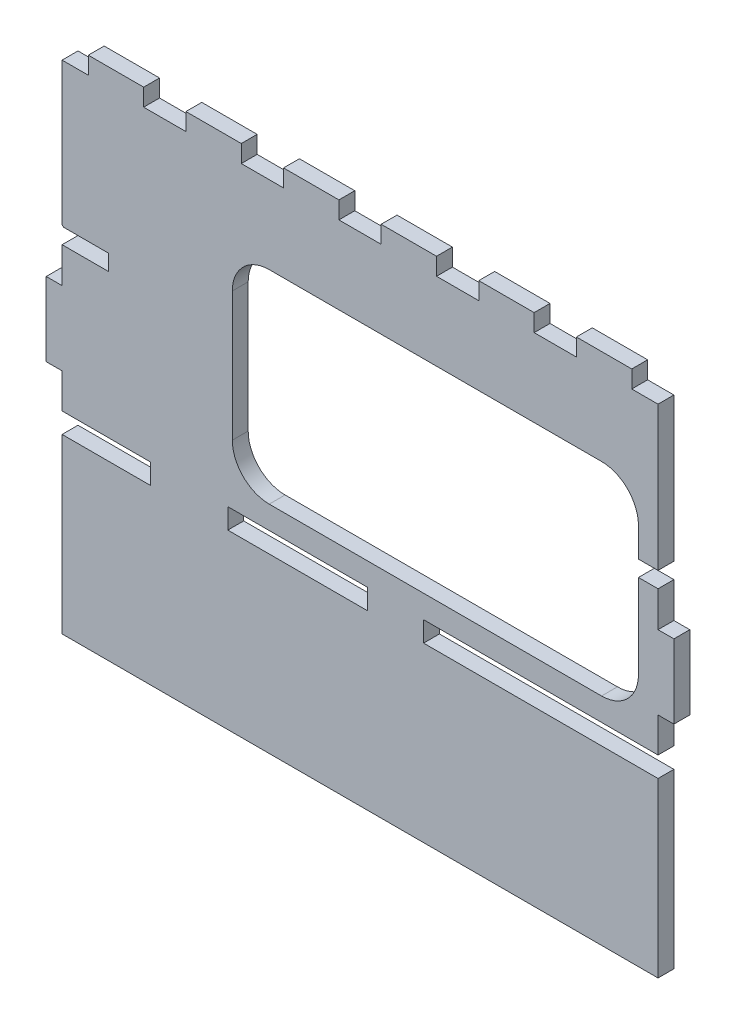
SolidWorks part; units mm, degrees
ref_plane "Front Plane" through (0, 0, 0) normal (0, 0, 1) x (1, 0, 0)
ref_plane "Top Plane" through (0, 0, 0) normal (0, 1, 0) x (1, 0, 0)
ref_plane "Right Plane" through (0, 0, 0) normal (1, 0, 0) x (0, 0, -1)
sketch "Sketch2" plane through (0, 0, 0) normal (0, 0, 1) x (1, 0, 0)
  line L1 (-73.61, 69.65) -> (-58.61, 69.65)
  line L2 (-85, 12.05) -> (-85, -7.95)
  line L3 (-80.7, -69.65) -> (80.7, -69.65)
  line L4 (85, 12.05) -> (85, -7.95)
  line L5 (32.15, 69.65) -> (47.15, 69.65)
  line L6 (58.59, 69.65) -> (73.59, 69.65)
  line L8 (-73.61, 69.65) -> (-73.61, 64.95)
  line L10 (-58.61, 69.65) -> (-58.61, 64.95)
  line L11 (-47.17, 69.65) -> (-47.17, 64.95)
  line L13 (-32.17, 69.65) -> (-32.17, 64.95)
  line L14 (-20.73, 69.65) -> (-20.73, 64.95)
  line L16 (-5.73, 69.65) -> (-5.73, 64.95)
  line L17 (5.71, 69.65) -> (5.71, 64.95)
  line L19 (20.71, 69.65) -> (20.71, 64.95)
  line L20 (32.15, 69.65) -> (32.15, 64.95)
  line L22 (47.15, 69.65) -> (47.15, 64.95)
  line L23 (58.59, 69.65) -> (58.59, 64.95)
  line L25 (73.59, 69.65) -> (73.59, 64.95)
  line L26 (-80.7, 64.95) -> (-80.7, 26.35)
  line L27 (-80.7, 64.95) -> (-80.7, 26.35) construction
  line L28 (-80.7, 12.05) -> (-85, 12.05)
  line L30 (-80.7, -7.95) -> (-85, -7.95)
  line L32 (80.7, 64.95) -> (80.7, 25.95)
  line L33 (80.7, -7.95) -> (80.7, -17.35)
  line L34 (80.7, 12.05) -> (85, 12.05)
  line L36 (80.7, -7.95) -> (85, -7.95)
  line L38 (-80.7, -7.95) -> (-80.7, -17.35)
  line L39 (5.71, 69.65) -> (20.71, 69.65)
  line L40 (-20.73, 69.65) -> (-5.73, 69.65)
  line L41 (-47.17, 69.65) -> (-32.17, 69.65)
  line L42 (80.7, 64.95) -> (73.59, 64.95)
  line L43 (58.59, 64.95) -> (47.15, 64.95)
  line L44 (60.4, 21.65) -> (75.4, 21.65) construction
  line L46 (32.15, 64.95) -> (20.71, 64.95)
  line L48 (5.71, 64.95) -> (-5.73, 64.95)
  line L50 (-20.73, 64.95) -> (-32.17, 64.95)
  line L52 (-47.17, 64.95) -> (-58.61, 64.95)
  line L53 (-73.61, 64.95) -> (-80.7, 64.95)
  line L54 (-80.318, 25.95) -> (-80.7, 26.35)
  line L57 (79.9, 25.95) -> (75.4, 25.95)
  line L59 (80.282, 21.65) -> (75.4, 21.65)
  line L60 (75.4, 25.95) -> (75.4, 21.65)
  line L65 (-68.2, 25.95) -> (-80.318, 25.95)
  line L66 (-68.2, 25.95) -> (-68.2, 21.65)
  line L67 (-68.2, 21.65) -> (-80.7, 21.65)
  line L83 (65.4, 43.85) -> (-24.6, 43.85)
  line L84 (75.4, 33.85) -> (75.4, -1.15)
  line L85 (65.4, -11.15) -> (-24.6, -11.15)
  line L86 (-34.6, 33.85) -> (-34.6, -1.15)
  line L88 (-80.7, 22.05) -> (-80.7, 21.65)
  line L89 (-80.7, 22.05) -> (-80.7, 12.05)
  line L90 (-80.7, 22.05) -> (-80.7, 12.05) construction
  line L91 (79.9, 25.95) -> (80.7, 25.95)
  line L93 (80.7, 21.65) -> (80.282, 21.65)
  line L94 (80.7, 21.65) -> (80.7, 12.05)
  line L97 (80.7, -22.85) -> (80.7, -69.65)
  line L98 (-35.818, -17.35) -> (1.952, -17.35)
  line L100 (-80.7, -22.85) -> (-80.7, -69.65)
  line L101 (80.7, -17.35) -> (17.2, -17.35)
  line L103 (80.7, -22.85) -> (17.2, -22.85)
  line L104 (17.2, -17.35) -> (17.2, -22.85)
  line L105 (1.952, -22.85) -> (1.952, -17.35)
  line L106 (-35.818, -22.85) -> (1.952, -22.85)
  line L107 (-35.818, -22.85) -> (-35.818, -17.35)
  line L109 (-80.7, -22.85) -> (-56.7296, -22.85)
  line L111 (-80.7, -17.35) -> (-56.7296, -17.35)
  line L112 (-56.7296, -22.85) -> (-56.7296, -17.35)
  arc A0 (75.4, 33.85) -> (65.4, 43.85) centre (65.4, 33.85) ccw
  arc A1 (65.4, -11.15) -> (75.4, -1.15) centre (65.4, -1.15) ccw
  arc A2 (-24.6, 43.85) -> (-34.6, 33.85) centre (-24.6, 33.85) ccw
  arc A3 (-34.6, -1.15) -> (-24.6, -11.15) centre (-24.6, -1.15) ccw
  point P1 (0, 0)
  point P50 (67.9, 21.65)
  point P59 (17.2, -20.1)
  point P64 (-16.933, -22.85)
  dimension "D16" = 10
  dimension "D17" = 90
  dimension "D1" = 0
  dimension "D2" = 161.4
  dimension "D3" = 139.3
  dimension "D4" = 15
  dimension "D5" = 4.7
  dimension "D6" = 11.39
  dimension "D8" = 11.44
  dimension "D9" = 57.6
  dimension "D10" = 4.3
  dimension "D11" = 20
  dimension "D12" = 4.3
  dimension "D13" = 69.65
  dimension "D14" = 80.7
  dimension "D15" = 20
  dimension "D18" = 55
  dimension "D19" = 58.5
  dimension "D20" = 5.5
  dimension "D21" = 63.5
  dimension "D22" = 49.55
  dimension "D23" = 37.77
  dimension "D24" = 63.767
  dimension "D25" = 23.9704
  dimension "D7" = 6
extrude "Boss-Extrude1" add sketch "Sketch2" along normal blind 4.3
